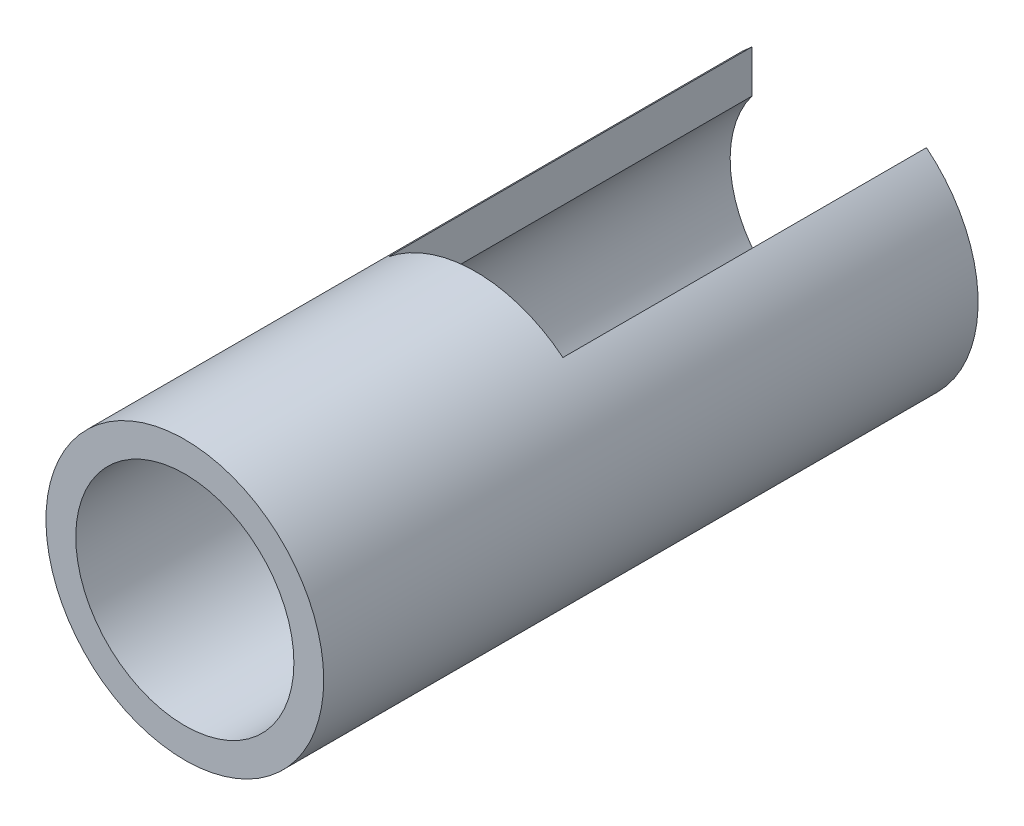
SolidWorks part; units mm, degrees
ref_plane "Front Plane" through (0, 0, 0) normal (0, 0, 1) x (1, 0, 0)
ref_plane "Top Plane" through (0, 0, 0) normal (0, 1, 0) x (1, 0, 0)
ref_plane "Right Plane" through (0, 0, 0) normal (1, 0, 0) x (0, 0, -1)
sketch "Sketch1" plane through (0, 0, 0) normal (0, 0, 1) x (1, 0, 0)
  circle A0 centre (0, 0) radius 24.257
  circle A1 centre (0, 0) radius 19.05
  dimension "D1" = 38.1
  dimension "D2" = 48.514
extrude "Boss-Extrude1" add sketch "Sketch1" along normal blind 114.3
sketch "Sketch2" plane through (0, 0, 0) normal (0, 1, 0) x (1, 0, 0)
  line L0 (0, 0) -> (0, -31.75) construction
  line L2 (-15.24, -63.5) -> (15.24, -63.5)
  line L3 (-15.24, -63.5) -> (-15.24, 0)
  line L4 (-15.24, 0) -> (15.24, 0)
  line L5 (15.24, -63.5) -> (15.24, 0)
  line L6 (-15.24, -63.5) -> (15.24, 0) construction
  line L7 (-15.24, 0) -> (15.24, -63.5) construction
  dimension "D1" = 30.48
  dimension "D2" = 31.75
  dimension "D3" = 63.5
extrude "Cut-Extrude1" cut sketch "Sketch2" against normal blind 2.54 and the other way through all
equation "\"D2@Sketch1\"=1.91"
